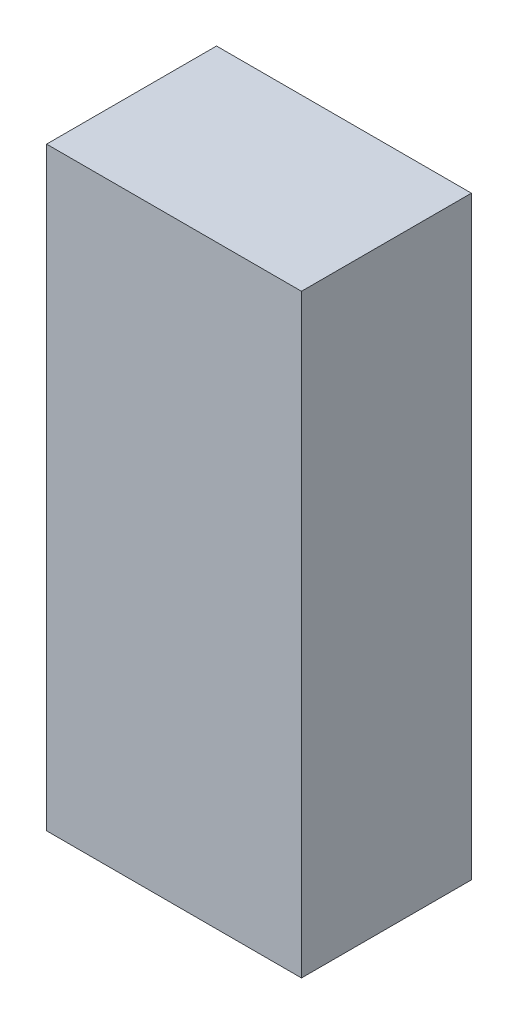
SolidWorks part; units mm, degrees
ref_plane "Front Plane" through (0, 0, 0) normal (0, 0, 1) x (1, 0, 0)
ref_plane "Top Plane" through (0, 0, 0) normal (0, 1, 0) x (1, 0, 0)
ref_plane "Right Plane" through (0, 0, 0) normal (1, 0, 0) x (0, 0, -1)
sketch "Sketch1" plane through (0, 0, 0) normal (0, 1, 0) x (1, 0, 0)
  line L1 (-1.5, 1) -> (1.5, 1)
  line L2 (-1.5, 1) -> (-1.5, -1)
  line L3 (-1.5, -1) -> (1.5, -1)
  line L4 (1.5, 1) -> (1.5, -1)
  line L5 (-1.5, 1) -> (1.5, -1) construction
  line L6 (-1.5, -1) -> (1.5, 1) construction
  point P0 (0, 0)
  dimension "D1" = 2
  dimension "D2" = 3
extrude "Boss-Extrude1" add sketch "Sketch1" along normal blind 7
